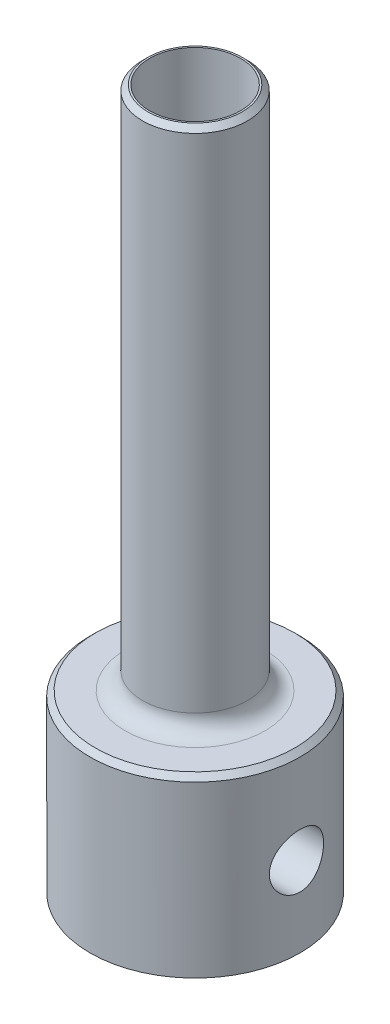
SolidWorks part; units mm, degrees
ref_plane "Front Plane" through (0, 0, 0) normal (0, 0, 1) x (1, 0, 0)
ref_plane "Top Plane" through (0, 0, 0) normal (0, 1, 0) x (1, 0, 0)
ref_plane "Right Plane" through (0, 0, 0) normal (1, 0, 0) x (0, 0, -1)
sketch "Sketch6" plane through (0, 0, 0) normal (0, 1, 0) x (1, 0, 0)
  circle A0 centre (0, 0) radius 6
extrude "Boss-Extrude4" add sketch "Sketch6" along normal blind 10
sketch "Sketch7" plane through (0, 10, 0) normal (0, 1, 0) x (1, 0, 0)
  circle A0 centre (0, 0) radius 3
  dimension "D1" = 6
extrude "Boss-Extrude5" add sketch "Sketch7" along normal blind 30
chamfer "Chamfer1" distance 0.3 angle 45 1 edges at (0, 40, 3)
chamfer "Chamfer2" distance 0.3 angle 45 1 edges at (0, 10, 6)
ref_plane "Plane5" through (-6, 0, 0) normal (-1, 0, 0) x (0, 0, 1)
sketch "Sketch10" plane through (-6, 0, 0) normal (-1, 0, 0) x (0, 0, 1)
  circle A0 centre (0, 4.5671) radius 1.55
extrude "Cut-Extrude4" cut sketch "Sketch10" against normal through all both and the other way through all contours A0
sketch "Sketch11" plane through (0, 40, 0) normal (0, 1, 0) x (1, 0, 0)
  circle A0 centre (0, 0) radius 2.6
  dimension "D1" = 5.2
extrude "Cut-Extrude5" cut sketch "Sketch11" against normal through all and the other way through all
fillet "Fillet1" radius 1 1 edges at (0, 10, 3)
